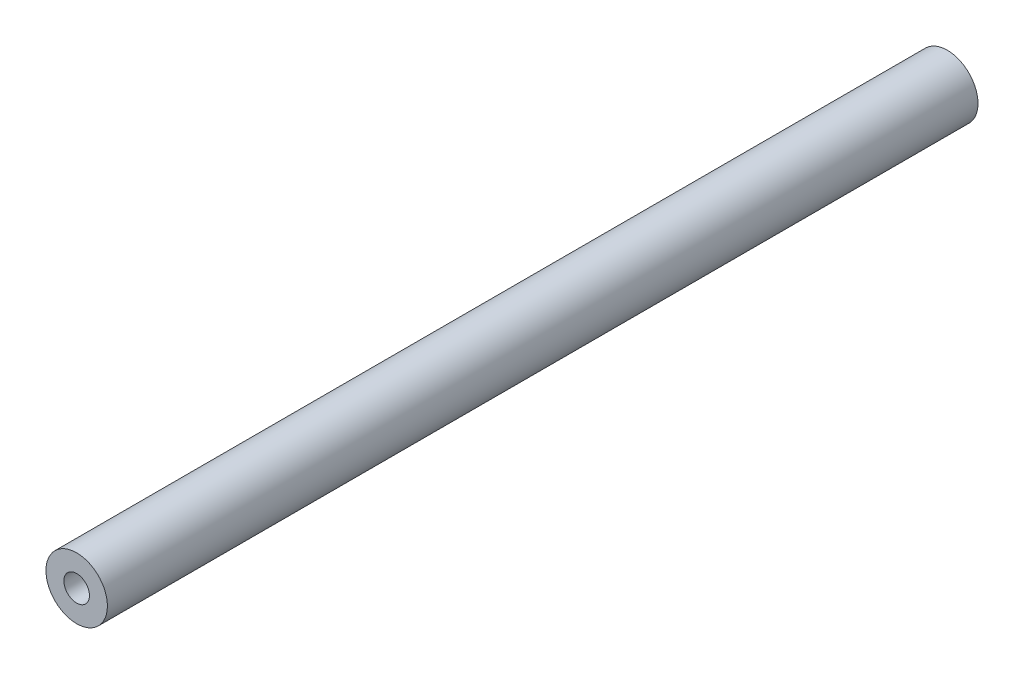
SolidWorks part; units mm, degrees
ref_plane "Plano frontal" through (0, 0, 0) normal (0, 0, 1) x (1, 0, 0)
ref_plane "Plano superior" through (0, 0, 0) normal (0, 1, 0) x (1, 0, 0)
ref_plane "Plano direito" through (0, 0, 0) normal (1, 0, 0) x (0, 0, -1)
sketch "Esboço1" plane through (0, 0, 0) normal (0, 0, 1) x (1, 0, 0)
  circle A0 centre (0, 0) radius 3
  dimension "D1" = 6
extrude "Ressalto-extrusão1" add sketch "Esboço1" along normal blind 85
hole_wizard "Broca de rosquear para tarraxa de M31" positions "3DSketch1" profile "Esboço2" hole size "M3" standard "ISO"
sketch3d "3DSketch1"
  line L0 (0, 0, 85) -> (0, 0, 0) construction
  point P0 (0, 0, 85)
  point P4 (0, 0, 0)
sketch "Esboço2" plane through (0, 0, 85) normal (1, 0, 0) x (0, -1, 0)
  line L0 (0, 0) -> (0, 8.7511)
  line L1 (0, 8.7511) -> (1.25, 8)
  line L2 (1.25, 8) -> (1.25, 0)
  line L5 (1.25, 0) -> (0, 0)
  line L10 (0, 8.7511) -> (-1.25, 8) construction
  line L11 (0, -6.35) -> (0, 107.95) construction
  dimension "Hole Dia." = 2.5
  dimension "Hole Depth" = 8
  dimension "Drill Angle" = 118
hole_wizard "Broca de rosquear para tarraxa de M32" positions "3DSketch2" profile "Esboço3" hole size "M3" standard "ISO"
sketch3d "3DSketch2"
  point P0 (0, 0, 0)
sketch "Esboço3" plane through (0, 0, 0) normal (1, 0, 0) x (0, 1, 0)
  line L0 (0, 0) -> (0, 8.7511)
  line L1 (0, 8.7511) -> (1.25, 8)
  line L2 (1.25, 8) -> (1.25, 0)
  line L5 (1.25, 0) -> (0, 0)
  line L10 (0, 8.7511) -> (-1.25, 8) construction
  line L11 (0, -6.35) -> (0, 107.95) construction
  dimension "Hole Dia." = 2.5
  dimension "Hole Depth" = 8
  dimension "Drill Angle" = 118
